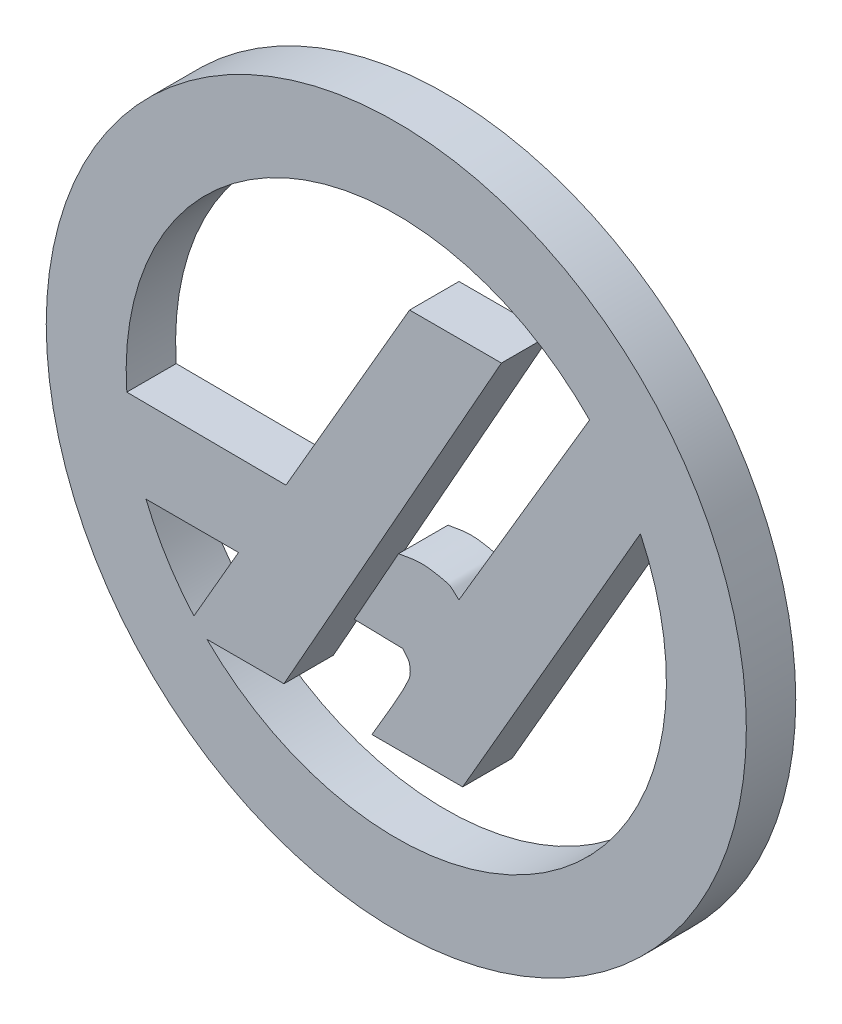
SolidWorks part; units mm, degrees
ref_plane "Front Plane" through (0, 0, 0) normal (0, 0, 1) x (1, 0, 0)
ref_plane "Top Plane" through (0, 0, 0) normal (0, 1, 0) x (1, 0, 0)
ref_plane "Right Plane" through (0, 0, 0) normal (1, 0, 0) x (0, 0, -1)
sketch "Sketch1" plane through (0, 0, 0) normal (0, 0, 1) x (1, 0, 0)
  line L0 (153.6667, 407) -> (768.3333, 407) construction
  line L1 (136.6667, 381.5) -> (683.3333, 381.5) construction
  line L5 (652.1845, 561.6969) -> (520, 338)
  line L6 (459, 348) -> (414.1531, 268)
  line L7 (414.1531, 268) -> (463, 267)
  line L8 (432, 176) -> (523.7837, 176)
  line L9 (523.7837, 176) -> (703.6075, 487.7876)
  line L10 (264.9969, 175.9694) -> (342.9994, 176)
  line L11 (342.9994, 176) -> (563, 567)
  line L12 (563, 567) -> (470.0808, 567)
  line L13 (470.0808, 567) -> (345, 351)
  line L14 (345, 351) -> (184, 352)
  line L15 (203.4239, 268) -> (297, 268)
  line L16 (297, 268) -> (251.8843, 189.7995)
  arc A1 (203.4239, 268) -> (251.8843, 189.7995) centre (456.634, 370.7972) ccw
  arc A2 (264.9969, 175.9694) -> (703.6075, 487.7876) centre (456.634, 370.7972) ccw
  arc A3 (652.1845, 561.6969) -> (184, 352) centre (456.634, 370.7972) ccw
  circle A5 centre (456.634, 370.7972) radius 354.1542
  spline S2 degree 3 poles (520, 338) (516, 341) (512.8565, 345.8107) (508, 347) (483.2942, 353.0504) (477.8517, 351.142) (459, 348) knots 0 0 0 0 1 1 1 2 2 2 2
  spline S3 degree 3 poles (463, 267) (465.3333, 263.6667) (469.0504, 260.9565) (470, 257) (471.1695, 252.1273) (471.1283, 246.5367) (469, 242) (458.288, 219.1666) (444.3333, 198) (432, 176) knots 0 0 0 0 1 1 1 2 2 2 3 3 3 3
  point P4 (544.5589, 27.7509)
extrude "Boss-Extrude4" add sketch "Sketch1" along normal blind 50
